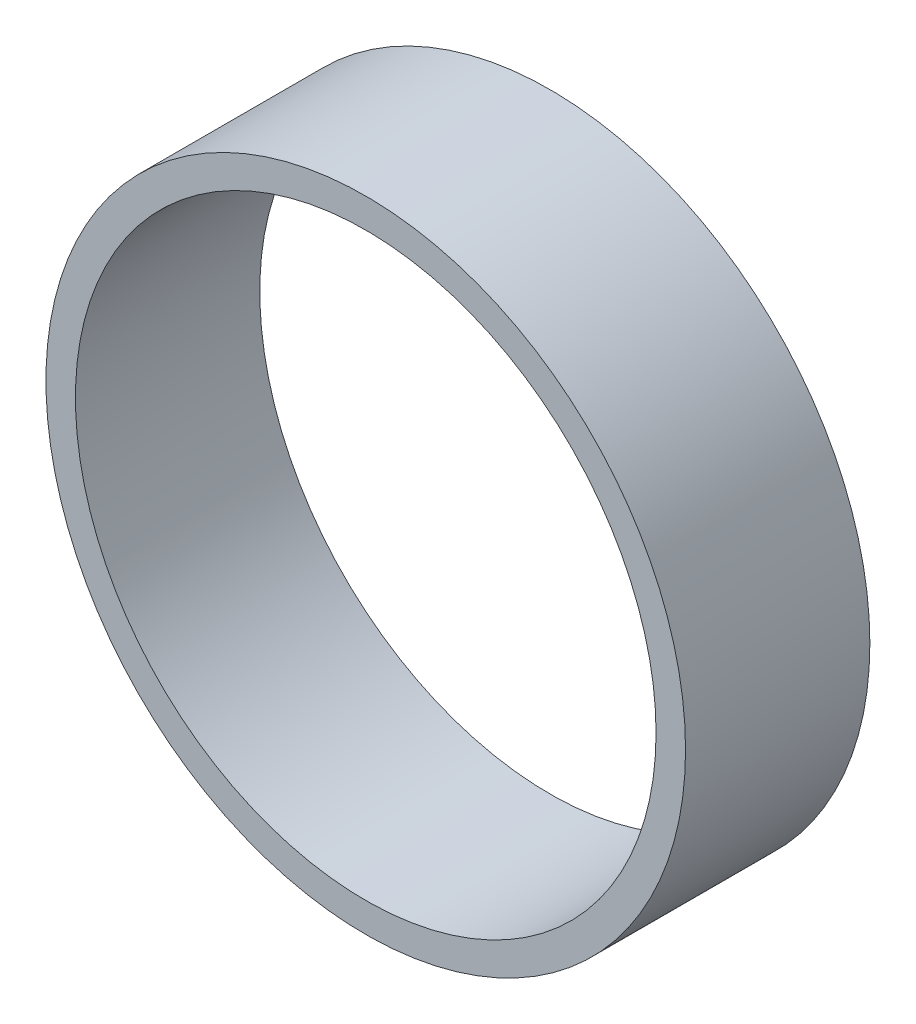
SolidWorks part; units mm, degrees
ref_plane "Front Plane" through (0, 0, 0) normal (0, 0, 1) x (1, 0, 0)
ref_plane "Top Plane" through (0, 0, 0) normal (0, 1, 0) x (1, 0, 0)
ref_plane "Right Plane" through (0, 0, 0) normal (1, 0, 0) x (0, 0, -1)
sketch "Sketch1" plane through (0, 0, 0) normal (0, 0, 1) x (1, 0, 0)
  circle A0 centre (0, 0) radius 34.7
  circle A1 centre (0, 0) radius 31.5
  dimension "BottleBore" = 63
extrude "Bottle_collar" add sketch "Sketch1" along normal blind 20
